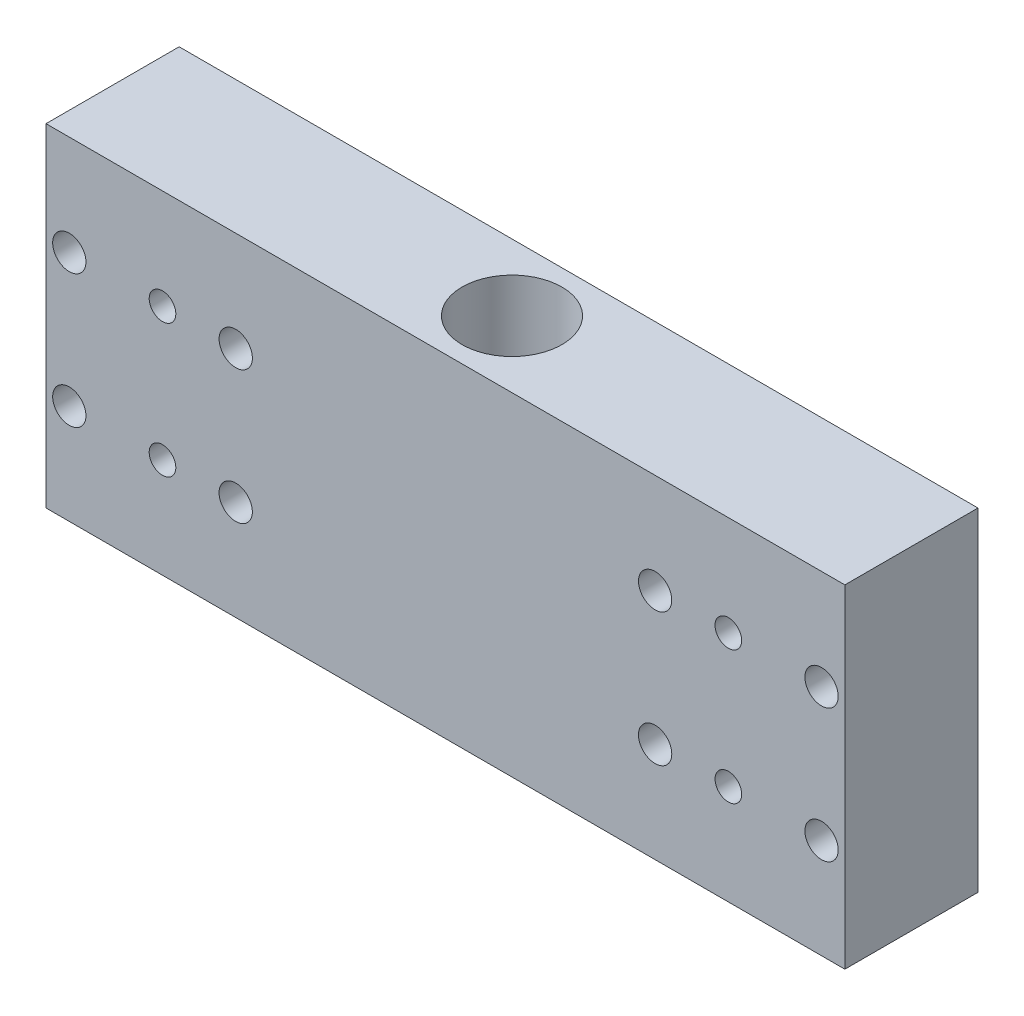
SolidWorks part; units mm, degrees
ref_plane "Front Plane" through (0, 0, 0) normal (0, 0, 1) x (1, 0, 0)
ref_plane "Top Plane" through (0, 0, 0) normal (0, 1, 0) x (1, 0, 0)
ref_plane "Right Plane" through (0, 0, 0) normal (1, 0, 0) x (0, 0, -1)
sketch "Sketch1" plane through (0, 0, 0) normal (0, 0, 1) x (1, 0, 0)
  line L1 (60, -25) -> (-60, -25)
  line L2 (60, -25) -> (60, 25)
  line L3 (60, 25) -> (-60, 25)
  line L4 (-60, -25) -> (-60, 25)
  line L5 (60, -25) -> (-60, 25) construction
  line L6 (60, 25) -> (-60, -25) construction
  point P0 (0, 0)
  dimension "D1" = 120
  dimension "D2" = 50
extrude "Boss-Extrude1" add sketch "Sketch1" along normal blind 20
sketch "Sketch2" plane through (0, 0, 20) normal (0, 0, 1) x (1, 0, 0)
  line L0 (0, 25) -> (0, -25) construction
  line L1 (60, 25) -> (-60, 25) construction
  line L2 (-44, 25) -> (-44, -25) construction
  line L3 (-60, -25) -> (60, -25) construction
  line L4 (-28, 25) -> (-28, -25) construction
  line L5 (-60, 25) -> (-60, -25) construction
  line L6 (-60, 0) -> (0, 0) construction
  circle A0 centre (-56.5, 10) radius 1.25
  circle A1 centre (-31.5, 10) radius 1.25
  circle A2 centre (-56.5, -10) radius 1.25
  circle A3 centre (-31.5, -10) radius 1.25
  circle A4 centre (56.5, -10) radius 1.25
  circle A5 centre (31.5, -10) radius 1.25
  circle A6 centre (31.5, 10) radius 1.25
  circle A7 centre (56.5, 10) radius 1.25
  dimension "D3" = 25
  dimension "D4" = 20
  dimension "D5" = 2.5
  dimension "D1" = 32
  dimension "D2" = 16
extrude "Cut-Extrude1" cut sketch "Sketch2" against normal through all both and the other way through all
sketch "Sketch3" plane through (0, 0, 20) normal (0, 0, 1) x (1, 0, 0)
  line L0 (0, 25) -> (0, 0) construction
  line L1 (60, 25) -> (-60, 25) construction
  line L2 (0, 0) -> (-60, 0) construction
  line L3 (-60, 25) -> (-60, -25) construction
  circle A0 centre (-56.5, 10) radius 2.5
  circle A1 centre (-31.5, 10) radius 2.5
  circle A2 centre (-56.5, -10) radius 2.5
  circle A3 centre (-31.5, -10) radius 2.5
  circle A4 centre (56.5, 10) radius 2.5
  circle A5 centre (31.5, 10) radius 2.5
  circle A6 centre (31.5, -10) radius 2.5
  circle A7 centre (56.5, -10) radius 2.5
  dimension "D1" = 5
extrude "Cut-Extrude2" cut sketch "Sketch3" against normal blind 5
sketch "Sketch4" plane through (0, 25, 0) normal (0, 1, 0) x (1, 0, 0)
  line L0 (-60, -10) -> (60, -10) construction
  line L1 (-60, -20) -> (-60, 0) construction
  line L2 (60, -20) -> (60, 0) construction
  circle A0 centre (0, -10) radius 7.5
  dimension "D1" = 15
extrude "Cut-Extrude3" cut sketch "Sketch4" against normal up to next
sketch "Sketch5" plane through (0, 0, 20) normal (0, 0, 1) x (1, 0, 0)
  line L0 (0, 25) -> (0, 0) construction
  line L1 (60, 25) -> (-60, 25) construction
  line L2 (0, 0) -> (60, 0) construction
  line L3 (60, -25) -> (60, 25) construction
  circle A0 centre (42.5, 10) radius 2
  circle A1 centre (42.5, -10) radius 2
  circle A2 centre (-42.5, -10) radius 2
  circle A3 centre (-42.5, 10) radius 2
  dimension "D1" = 20
  dimension "D2" = 85
  dimension "D3" = 4
extrude "Cut-Extrude4" cut sketch "Sketch5" against normal up to next
